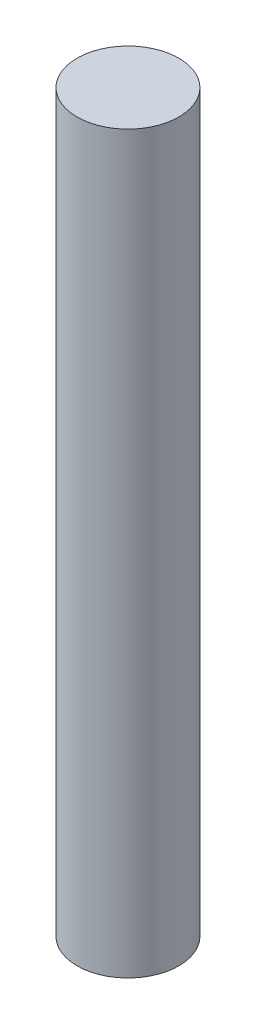
SolidWorks part; units mm, degrees
ref_plane "Front Plane" through (0, 0, 0) normal (0, 0, 1) x (1, 0, 0)
ref_plane "Top Plane" through (0, 0, 0) normal (0, 1, 0) x (1, 0, 0)
ref_plane "Right Plane" through (0, 0, 0) normal (1, 0, 0) x (0, 0, -1)
sketch "Sketch1" plane through (0, 0, 0) normal (0, 1, 0) x (1, 0, 0)
  circle A1 centre (0, 0) radius 49.149
  dimension "D1" = 98.298
extrude "Boss-Extrude1" add sketch "Sketch1" along normal blind 709.676
